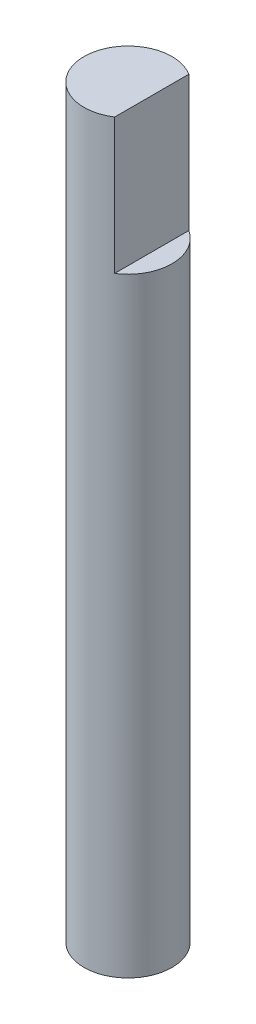
SolidWorks part; units mm, degrees
ref_plane "Front Plane" through (0, 0, 0) normal (0, 0, 1) x (1, 0, 0)
ref_plane "Top Plane" through (0, 0, 0) normal (0, 1, 0) x (1, 0, 0)
ref_plane "Right Plane" through (0, 0, 0) normal (1, 0, 0) x (0, 0, -1)
sketch "Sketch1" plane through (0, 0, 0) normal (0, 1, 0) x (1, 0, 0)
  circle A0 centre (0, 0) radius 0.65
  dimension "D1" = 1.3
extrude "Boss-Extrude1" add sketch "Sketch1" along normal blind 11
sketch "Sketch2" plane through (0, 11, 0) normal (0, 1, 0) x (1, 0, 0)
  line L0 (0.35, 0.5477) -> (0.35, -0.5477)
  circle A0 centre (0, 0) radius 0.65
  circle M2 centre (0, 0) radius 0.65
  dimension "D2" = 1.3
  dimension "D1" = 0.35
extrude "Cut-Extrude1" cut sketch "Sketch2" against normal blind 2 contours L0 M2
